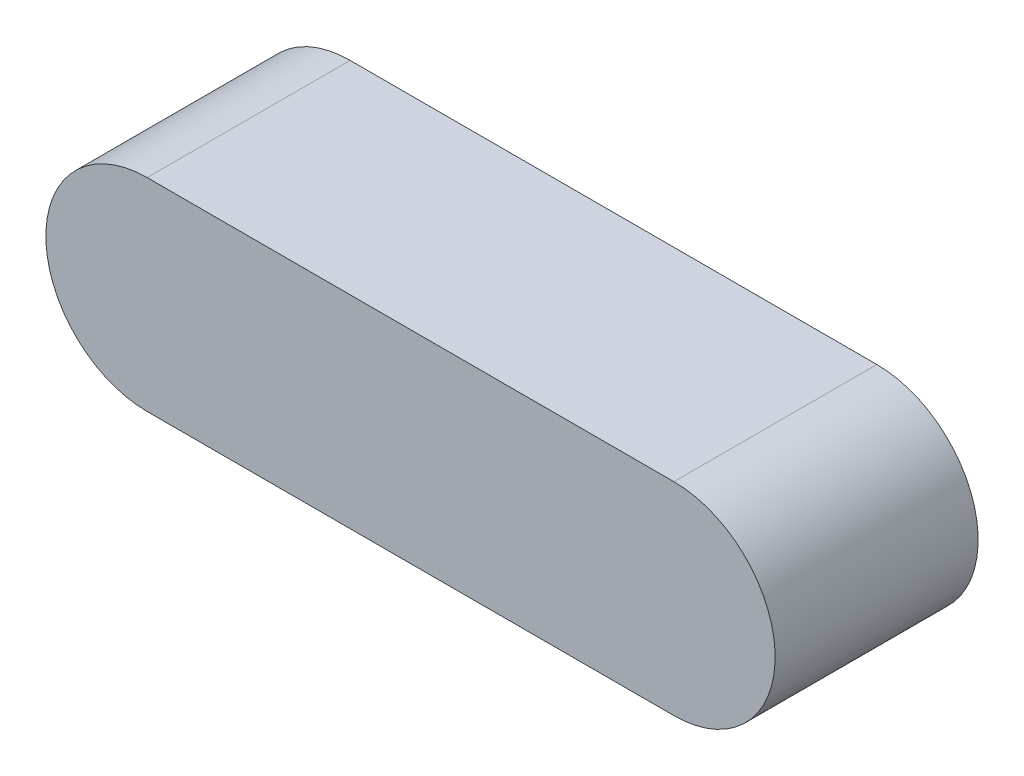
SolidWorks part; units mm, degrees
ref_plane "前视基准面" through (0, 0, 0) normal (0, 0, 1) x (1, 0, 0)
ref_plane "上视基准面" through (0, 0, 0) normal (0, 1, 0) x (1, 0, 0)
ref_plane "右视基准面" through (0, 0, 0) normal (1, 0, 0) x (0, 0, -1)
sketch "草图1" plane through (0, 0, 0) normal (0, 0, 1) x (1, 0, 0)
  line L0 (-32.5, 0) -> (32.5, 0) construction
  line L1 (-32.5, 12.5) -> (32.5, 12.5)
  line L2 (-32.5, -12.5) -> (32.5, -12.5)
  arc A0 (-32.5, 12.5) -> (-32.5, -12.5) centre (-32.5, 0) ccw
  arc A1 (32.5, -12.5) -> (32.5, 12.5) centre (32.5, 0) ccw
  point P3 (0, 0)
  point P9 (45, 0)
  point P10 (-45, 0)
  dimension "D1" = 25
  dimension "D2" = 90
extrude "凸台-拉伸1" add sketch "草图1" along normal blind 25.05
sketch "草图2" plane through (0, 0, 0) normal (0, 0, -1) x (-1, 0, 0)
  line L0 (-22.5, 0) -> (22.5, 0) construction
  circle A0 centre (-22.5, 0) radius 1.5
  circle A1 centre (22.5, 0) radius 1.5
  point P4 (0, 0)
  dimension "D2" = 3
  dimension "D3" = 3
  dimension "D1" = 45
extrude "切除-拉伸1" cut sketch "草图2" against normal blind 3
